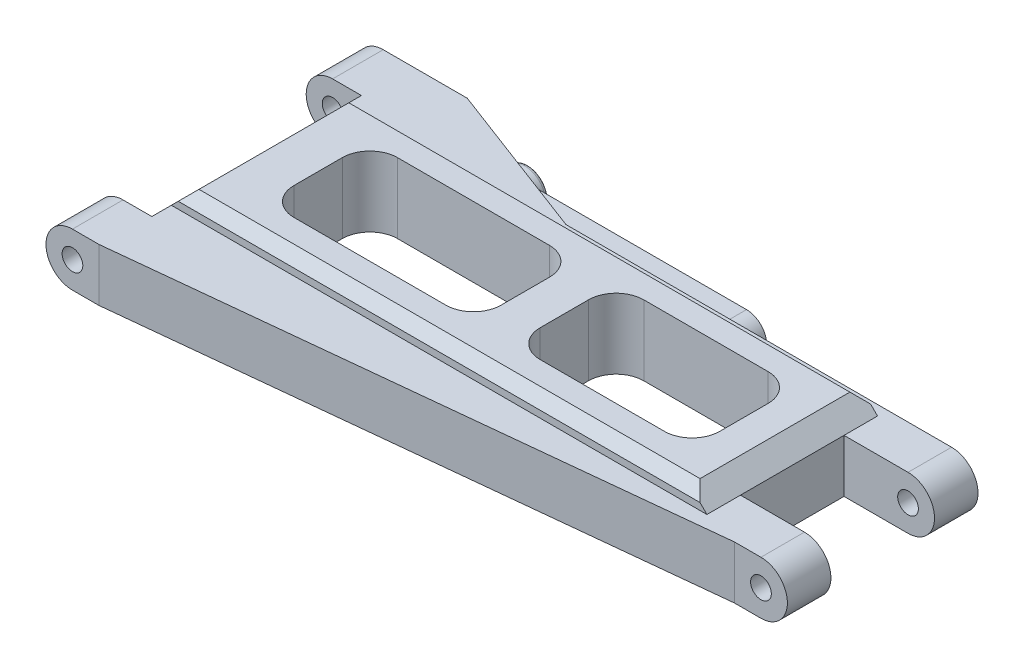
SolidWorks part; units mm, degrees
ref_plane "Front Plane" through (0, 0, 0) normal (0, 0, 1) x (1, 0, 0)
ref_plane "Top Plane" through (0, 0, 0) normal (0, 1, 0) x (1, 0, 0)
ref_plane "Right Plane" through (0, 0, 0) normal (1, 0, 0) x (0, 0, -1)
sketch "Sketch1" plane through (0, 0, 0) normal (0, 0, 1) x (1, 0, 0)
  line L0 (-45.5, 0) -> (45.5, 0) construction
  line L1 (-45.5, 3.83) -> (45.5, 3.83)
  line L2 (-45.5, -3.83) -> (45.5, -3.83)
  arc A0 (-45.5, 3.83) -> (-45.5, -3.83) centre (-45.5, 0) ccw
  arc A1 (45.5, -3.83) -> (45.5, 3.83) centre (45.5, 0) ccw
  circle A2 centre (-45.5, 0) radius 1.5
  circle A3 centre (45.5, 0) radius 1.5
  point P2 (0, 0)
  dimension "D3" = 3
  dimension "D1" = 7.66
  dimension "D2" = 91
extrude "Boss-Extrude1" add sketch "Sketch1" along normal mid plane 45
sketch "Sketch2" plane through (0, 3.83, 0) normal (0, 1, 0) x (1, 0, 0)
  line L0 (-41.67, -22.5) -> (41.67, -13.8)
  line L1 (45.5, -22.5) -> (-45.5, -22.5) construction
  line L2 (41.67, -13.8) -> (49.33, -13.8)
  line L3 (49.33, -22.5) -> (49.33, 22.5) construction
  line L4 (49.33, -13.8) -> (49.33, -22.5)
  line L5 (49.33, -22.5) -> (-41.67, -22.5)
  line L6 (-49.33, -22.5) -> (-45.5, -22.5) construction
  line L7 (-49.33, -22.5) -> (-45.5, -22.5)
  line L8 (-41.67, -22.5) -> (-45.5, -22.5)
  line L9 (45.5, -22.5) -> (49.33, -22.5) construction
  line L10 (45.5, -22.5) -> (49.33, -22.5)
  line L11 (45.5, -13.8) -> (41.67, -13.8)
  line L12 (-33.33, 22.5) -> (-10.33, 13.8)
  line L13 (45.5, 22.5) -> (-45.5, 22.5) construction
  line L14 (-10.33, 13.8) -> (49.33, 13.8)
  line L15 (49.33, 13.8) -> (49.33, 22.5)
  line L16 (49.33, 22.5) -> (-33.33, 22.5)
  line L17 (-49.33, 22.5) -> (-49.33, -22.5) construction
  line L19 (-6.43, 7.5) -> (-28.43, 7.5)
  line L20 (-2.43, 3.5) -> (-2.43, -3.5)
  line L21 (-6.43, -7.5) -> (-28.43, -7.5)
  line L22 (-32.43, 3.5) -> (-32.43, -3.5)
  line L23 (-2.43, 7.5) -> (-32.43, -7.5) construction
  line L24 (-2.43, -7.5) -> (-32.43, 7.5) construction
  line L25 (-41.33, -15.175) -> (-49.33, -15.175)
  line L26 (-41.33, -15.175) -> (-41.33, 15.175)
  line L27 (-41.33, 15.175) -> (-49.33, 15.175)
  line L28 (-49.33, -15.175) -> (-49.33, 15.175)
  line L29 (-41.33, -15.175) -> (-49.33, 15.175) construction
  line L30 (-41.33, 15.175) -> (-49.33, -15.175) construction
  line L31 (25.23, -7.5) -> (7.23, -7.5)
  line L32 (29.23, -3.5) -> (29.23, 3.5)
  line L33 (25.23, 7.5) -> (7.23, 7.5)
  line L34 (3.23, -3.5) -> (3.23, 3.5)
  line L35 (29.23, -7.5) -> (3.23, 7.5) construction
  line L36 (29.23, 7.5) -> (3.23, -7.5) construction
  line L37 (36.23, -7.5) -> (49.33, -7.5)
  line L38 (36.23, -7.5) -> (36.23, 7.5)
  line L39 (36.23, 7.5) -> (49.33, 7.5)
  line L40 (49.33, -7.5) -> (49.33, 7.5)
  line L41 (36.23, -7.5) -> (49.33, 7.5) construction
  line L42 (36.23, 7.5) -> (49.33, -7.5) construction
  arc A0 (-6.43, 7.5) -> (-2.43, 3.5) centre (-6.43, 3.5) cw
  arc A1 (-2.43, -3.5) -> (-6.43, -7.5) centre (-6.43, -3.5) cw
  arc A2 (-28.43, -7.5) -> (-32.43, -3.5) centre (-28.43, -3.5) cw
  arc A3 (-28.43, 7.5) -> (-32.43, 3.5) centre (-28.43, 3.5) ccw
  arc A4 (29.23, 3.5) -> (25.23, 7.5) centre (25.23, 3.5) ccw
  arc A5 (25.23, -7.5) -> (29.23, -3.5) centre (25.23, -3.5) ccw
  arc A6 (7.23, -7.5) -> (3.23, -3.5) centre (7.23, -3.5) cw
  arc A7 (7.23, 7.5) -> (3.23, 3.5) centre (7.23, 3.5) ccw
  point P23 (-17.43, 0)
  point P41 (-45.33, 0)
  point P47 (16.23, 0)
  point P62 (42.78, 0)
  line M11 (45.5, 22.5) -> (-45.5, 22.5)
  line M13 (-45.5, -22.5) -> (45.5, -22.5)
  line M14 (45.5, -22.5) -> (45.5, 22.5)
  dimension "D5" = 4
  dimension "D11" = 4
  dimension "D1" = 13.8
  dimension "D2" = 13.8
  dimension "D3" = 16
  dimension "D4" = 39
  dimension "D6" = 30
  dimension "D7" = 15
  dimension "D8" = 30.35
  dimension "D9" = 8
  dimension "D10" = 8.9
  dimension "D12" = 5.66
  dimension "D13" = 26
  dimension "D14" = 7
extrude "Cut-Extrude1" cut sketch "Sketch2" against normal through all contours L12 L14 M14 M11 | L2 L0 M13 M14 | L5 L4 L2 M14 | L15 L16 L14 M14 | L19 A3 L22 A2 L21 A1 L20 A0 | L33 A7 L34 A6 L31 A5 L32 A4 | L26 L27 L28 L25 | L37 L40 L39 L38
sketch "Sketch3" plane through (0, 0, 0) normal (0, 1, 0) x (1, 0, 0)
  line L0 (-41.33, -15.175) -> (-41.33, 15.175) construction
  line L1 (-41.33, -12.35) -> (36.23, -12.35)
  line L2 (-41.33, -12.35) -> (-41.33, 12.35)
  line L3 (-41.33, 12.35) -> (36.23, 12.35)
  line L4 (36.23, -12.35) -> (36.23, 12.35)
  line L5 (-41.33, -12.35) -> (36.23, 12.35) construction
  line L6 (-41.33, 12.35) -> (36.23, -12.35) construction
  line L7 (36.23, -7.5) -> (36.23, 7.5) construction
  line L13 (-6.43, 7.5) -> (-28.43, 7.5)
  line L14 (-2.43, -3.5) -> (-2.43, 3.5)
  line L15 (-28.43, -7.5) -> (-6.43, -7.5)
  line L16 (-32.43, 3.5) -> (-32.43, -3.5)
  line L17 (-6.43, 7.5) -> (-28.43, 7.5)
  line L18 (-2.43, -3.5) -> (-2.43, 3.5)
  line L19 (-28.43, -7.5) -> (-6.43, -7.5)
  line L20 (-32.43, 3.5) -> (-32.43, -3.5)
  line L21 (25.23, 7.5) -> (7.23, 7.5)
  line L22 (29.23, -3.5) -> (29.23, 3.5)
  line L23 (7.23, -7.5) -> (25.23, -7.5)
  line L24 (3.23, 3.5) -> (3.23, -3.5)
  line L25 (25.23, 7.5) -> (7.23, 7.5)
  line L26 (29.23, -3.5) -> (29.23, 3.5)
  line L27 (7.23, -7.5) -> (25.23, -7.5)
  line L28 (3.23, 3.5) -> (3.23, -3.5)
  arc A4 (-28.43, 7.5) -> (-32.43, 3.5) centre (-28.43, 3.5) ccw
  arc A5 (-2.43, 3.5) -> (-6.43, 7.5) centre (-6.43, 3.5) ccw
  arc A6 (-6.43, -7.5) -> (-2.43, -3.5) centre (-6.43, -3.5) ccw
  arc A7 (-32.43, -3.5) -> (-28.43, -7.5) centre (-28.43, -3.5) ccw
  arc A8 (-28.43, 7.5) -> (-32.43, 3.5) centre (-28.43, 3.5) ccw
  arc A9 (-2.43, 3.5) -> (-6.43, 7.5) centre (-6.43, 3.5) ccw
  arc A10 (-6.43, -7.5) -> (-2.43, -3.5) centre (-6.43, -3.5) ccw
  arc A11 (-32.43, -3.5) -> (-28.43, -7.5) centre (-28.43, -3.5) ccw
  arc A12 (7.23, 7.5) -> (3.23, 3.5) centre (7.23, 3.5) ccw
  arc A13 (29.23, 3.5) -> (25.23, 7.5) centre (25.23, 3.5) ccw
  arc A14 (25.23, -7.5) -> (29.23, -3.5) centre (25.23, -3.5) ccw
  arc A15 (3.23, -3.5) -> (7.23, -7.5) centre (7.23, -3.5) ccw
  arc A16 (7.23, 7.5) -> (3.23, 3.5) centre (7.23, 3.5) ccw
  arc A17 (29.23, 3.5) -> (25.23, 7.5) centre (25.23, 3.5) ccw
  arc A18 (25.23, -7.5) -> (29.23, -3.5) centre (25.23, -3.5) ccw
  arc A19 (3.23, -3.5) -> (7.23, -7.5) centre (7.23, -3.5) ccw
  point P0 (-2.55, 0)
  dimension "D1" = 24.7
  dimension "D2" = 0
  dimension "D3" = 0
extrude "Boss-Extrude2" add sketch "Sketch3" along normal offset from surface (6.33 mm away) 2.5 contours L1 L4 L3 L2 A19 L28 A16 L25 A17 L26 A18 L27 A11 L20 A8 L17 A9 L18 A10 L19 up to face at (-17.43, 3.83, 0) offset beyond the face yes
chamfer "Chamfer1" distance 2.5 angle 45 6 edges at (-41.33, 5.08, -12.35) (36.23, 5.08, 12.35) (36.23, 6.33, 0) (-41.33, 5.08, 12.35) (36.23, 5.08, -12.35) (-41.33, 6.33, 0)
chamfer "Chamfer2" distance 1.5 angle 45 2 edges at (-2.55, 6.33, 12.35) (-2.55, 6.33, -12.35)
sketch "Sketch4" plane through (0, 0, -13.8) normal (0, 0, -1) x (-1, 0, 0)
  line L0 (21.5, 0) -> (-12.5, 0) construction
  line L1 (21.5, -2.93) -> (-12.5, -2.93)
  line L2 (21.5, 2.93) -> (-12.5, 2.93)
  arc A0 (21.5, -2.93) -> (21.5, 2.93) centre (21.5, 0) ccw
  arc A1 (-12.5, 2.93) -> (-12.5, -2.93) centre (-12.5, 0) ccw
  point P2 (4.5, 0)
  point P10 (45.5, 0)
  dimension "D1" = 5.86
  dimension "D2" = 34
  dimension "D3" = 58
extrude "Boss-Extrude3" add sketch "Sketch4" along normal offset from surface (3.31 mm away) 4.76 up to face at (-2.55, 4.33, -12.35) offset beyond the face yes
sketch "Sketch5" plane through (0, 0, -17.11) normal (0, 0, -1) x (-1, 0, 0)
  circle A0 centre (21.5, 0) radius 3
  dimension "D1" = 6
extrude "Boss-Extrude4" add sketch "Sketch5" along normal blind 2.4
fillet "Fillet1" radius 0.5 1 edges at (-24.5, 0, -19.51)
sketch "Sketch6" plane through (0, 0, -19.51) normal (0, 0, -1) x (-1, 0, 0)
  line L0 (21.5, 0) -> (-12.5, 0) construction
  line L1 (-5.3, 0) -> (-12.5, 0) construction
  circle A0 centre (21.5, 0) radius 1.25
  circle A1 centre (9.1, 0) radius 1.25
  circle A2 centre (1.9, 0) radius 1.25
  circle A3 centre (-5.3, 0) radius 1.25
  circle A4 centre (-12.5, 0) radius 1.25
  circle A5 centre (-8.9, 0) radius 1.25
  dimension "D3" = 2.5
  dimension "D2" = 12.4
  dimension "D1" = 4
extrude "Cut-Extrude2" cut sketch "Sketch6" against normal blind 10
